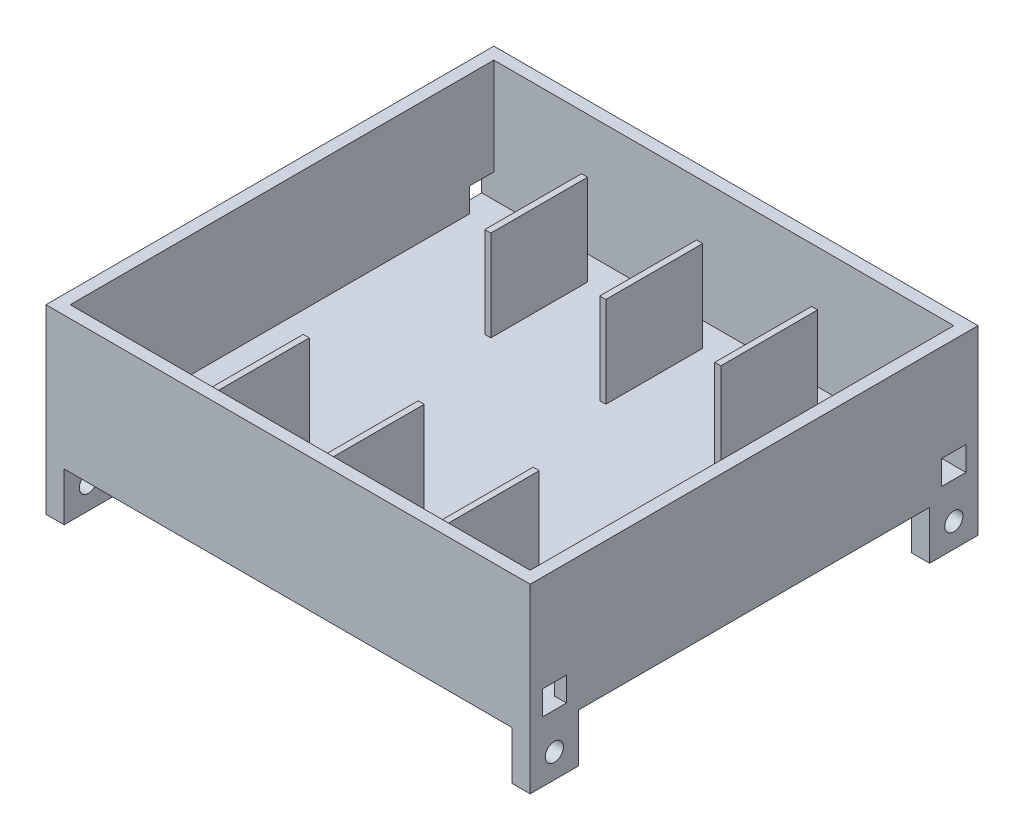
SolidWorks part; units mm, degrees
ref_plane "Front" through (0, 0, 0) normal (0, 0, 1) x (1, 0, 0)
ref_plane "Top" through (0, 0, 0) normal (0, 1, 0) x (1, 0, 0)
ref_plane "Right" through (0, 0, 0) normal (1, 0, 0) x (0, 0, -1)
sketch "Эскиз1" plane through (0, 0, 0) normal (0, 1, 0) x (1, 0, 0)
  line L1 (-40, 37) -> (40, 37)
  line L2 (-40, 37) -> (-40, -37)
  line L3 (-40, -37) -> (40, -37)
  line L4 (40, 37) -> (40, -37)
  line L5 (-40, 37) -> (40, -37) construction
  line L6 (-40, -37) -> (40, 37) construction
  point P0 (0, 0)
  dimension "D1" = 74
  dimension "D2" = 80
extrude "Бобышка-Вытянуть1" add sketch "Эскиз1" along normal blind 2
sketch "Эскиз2" plane through (0, 2, 0) normal (0, 1, 0) x (1, 0, 0)
  line L0 (40, 37) -> (-40, 37) construction
  line L1 (-38, 35) -> (38, 35)
  line L2 (-38, 35) -> (-38, -35)
  line L3 (-38, -35) -> (38, -35)
  line L4 (38, 35) -> (38, -35)
  line L5 (-38, 35) -> (38, -35) construction
  line L6 (-38, -35) -> (38, 35) construction
  line L7 (40, -37) -> (40, 37) construction
  point P0 (0, 0)
  line M3 (40, -37) -> (40, 37)
  line M4 (40, 37) -> (-40, 37)
  line M5 (-40, 37) -> (-40, -37)
  line M6 (-40, -37) -> (40, -37)
  dimension "D1" = 2
  dimension "D2" = 2
extrude "Бобышка-Вытянуть2" add sketch "Эскиз2" along normal blind 20 contours L1 L4 L3 L2 M6 M3 M4 M5
sketch "Эскиз3" plane through (0, 2, 0) normal (0, 1, 0) x (1, 0, 0)
  line L0 (-40, 37) -> (-40, -37) construction
  line L1 (-38, 35) -> (-40, 35)
  line L2 (-38, 35) -> (-38, 31)
  line L3 (-38, 31) -> (-40, 31)
  line L4 (-40, 35) -> (-40, 31)
  line L5 (40, -37) -> (40, 37) construction
  line L6 (38, 35) -> (40, 35)
  line L7 (38, 35) -> (38, 31)
  line L8 (38, 31) -> (40, 31)
  line L9 (40, 35) -> (40, 31)
  line L11 (38, -35) -> (40, -35)
  line L12 (38, -35) -> (38, -31)
  line L13 (38, -31) -> (40, -31)
  line L14 (40, -35) -> (40, -31)
  line L15 (-38, -35) -> (-40, -35)
  line L16 (-38, -35) -> (-38, -31)
  line L17 (-38, -31) -> (-40, -31)
  line L18 (-40, -35) -> (-40, -31)
  dimension "D1" = 4
extrude "Вырез-Вытянуть3" cut sketch "Эскиз3" along normal blind 4
sketch "Эскиз4" plane through (0, 2, 0) normal (0, 1, 0) x (1, 0, 0)
  line L0 (-40, -35) -> (40, -35) construction
  line L1 (-19.5, -35) -> (-18.5, -35)
  line L2 (-19.5, -35) -> (-19.5, -15)
  line L3 (-19.5, -15) -> (-18.5, -15)
  line L4 (-18.5, -35) -> (-18.5, -15)
  line L5 (-40, 35) -> (40, 35) construction
  line L6 (-0.5, -35) -> (0.5, -35)
  line L7 (-0.5, -35) -> (-0.5, -15)
  line L8 (-0.5, -15) -> (0.5, -15)
  line L9 (0.5, -35) -> (0.5, -15)
  line L10 (18.5, -35) -> (19.5, -35)
  line L11 (18.5, -35) -> (18.5, -15)
  line L12 (18.5, -15) -> (19.5, -15)
  line L13 (19.5, -35) -> (19.5, -15)
  line L14 (-19.5, 31) -> (19.5, 31)
  line L15 (-19.5, -31) -> (19.5, -31)
  line L18 (-19.5, 35) -> (-18.5, 33.5)
  line L19 (-19.5, 35) -> (-19.5, 15)
  line L20 (-19.5, 15) -> (-18.5, 15)
  line L21 (-18.5, 33.5) -> (-18.5, 15)
  line L22 (-19, -15) -> (-19, -35) construction
  line L23 (-0.5, 35) -> (0.5, 35)
  line L24 (-0.5, 35) -> (-0.5, 15)
  line L25 (-0.5, 15) -> (0.5, 15)
  line L26 (0.5, 35) -> (0.5, 15)
  line L27 (18.5, 35) -> (19.5, 35)
  line L28 (18.5, 35) -> (18.5, 15)
  line L29 (18.5, 15) -> (19.5, 15)
  line L30 (19.5, 35) -> (19.5, 15)
  line L35 (-38, 31) -> (-38, -31) construction
  line L36 (-38, 0) -> (38, 0) construction
  line L37 (38, 31) -> (38, -31) construction
  line L38 (0, -15) -> (0, -35) construction
  line L39 (19, -15) -> (19, -35) construction
  dimension "D1" = 1
  dimension "D2" = 19
  dimension "D3" = 20
  dimension "D4" = 19
  dimension "D5" = 19
  dimension "D6" = 4
  dimension "D7" = 4
extrude "Бобышка-Вытянуть3" add sketch "Эскиз4" along normal blind 15 contours L21 L14 L19 L20 | L26 L14 L24 L25 | L30 L14 L28 L29 | L2 L15 L4 L3 | L7 L15 L9 L8 | L13 L12 L11 L10
sketch "Эскиз6" plane through (0, 0, 0) normal (0, -1, 0) x (1, 0, 0)
  line L0 (0, 37) -> (0, -37) construction
  line L1 (40, 37) -> (37, 37)
  line L2 (40, 37) -> (40, 29)
  line L3 (40, 29) -> (37, 29)
  line L4 (37, 37) -> (37, 29)
  line L5 (40, -37) -> (37, -37)
  line L6 (40, -37) -> (40, -29)
  line L7 (40, -29) -> (37, -29)
  line L8 (37, -37) -> (37, -29)
  line L9 (-40, -37) -> (-37, -37)
  line L10 (-40, -37) -> (-40, -29)
  line L11 (-40, -29) -> (-37, -29)
  line L12 (-37, -37) -> (-37, -29)
  line L13 (-40, 37) -> (-37, 37)
  line L14 (-40, 37) -> (-40, 29)
  line L15 (-40, 29) -> (-37, 29)
  line L16 (-37, 37) -> (-37, 29)
  line L17 (-40, 37) -> (40, 37) construction
  line L18 (40, -37) -> (-40, -37) construction
  line L19 (-40, 0) -> (40, 0) construction
  line L20 (-40, -37) -> (-40, 37) construction
  line L21 (40, 37) -> (40, -37) construction
  dimension "D1" = 8
  dimension "D2" = 3
extrude "Бобышка-Вытянуть4" add sketch "Эскиз6" along normal blind 8
sketch "Эскиз7" plane through (-40, 0, 0) normal (-1, 0, 0) x (0, 0, 1)
  line L0 (37, -8) -> (29, -8) construction
  line L1 (37, 22) -> (37, -8) construction
  line L2 (-29, -8) -> (-29, 0) construction
  line L3 (-29, -8) -> (-37, -8) construction
  circle A0 centre (33, -4) radius 1.5
  circle A1 centre (-33, -4) radius 1.5
  point P4 (33, -8)
  dimension "D1" = 3
  dimension "D2" = 3
  dimension "D3" = 4
  dimension "D4" = 4
  dimension "D5" = 4
  dimension "D6" = 4
extrude "Вырез-Вытянуть5" cut sketch "Эскиз7" against normal through all
